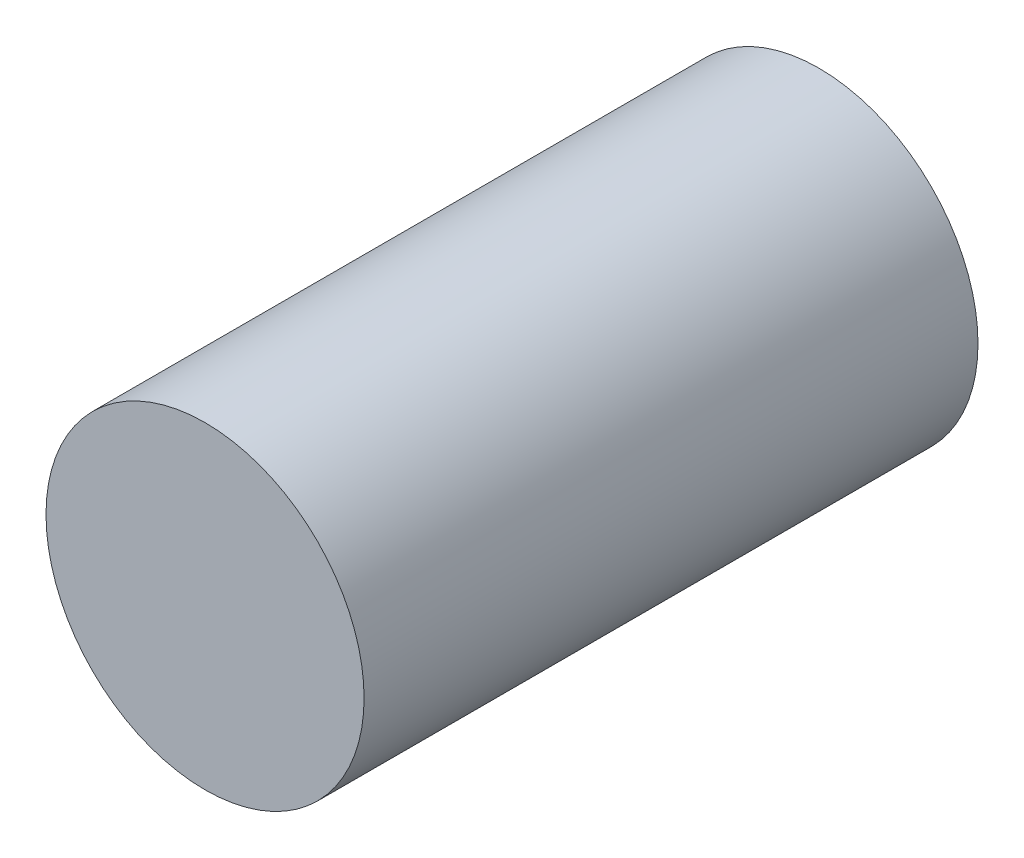
SolidWorks part; units mm, degrees
ref_plane "Płaszczyzna przednia" through (0, 0, 0) normal (0, 0, 1) x (1, 0, 0)
ref_plane "Płaszczyzna górna" through (0, 0, 0) normal (0, 1, 0) x (1, 0, 0)
ref_plane "Płaszczyzna prawa" through (0, 0, 0) normal (1, 0, 0) x (0, 0, -1)
sketch "Sketch1" plane through (0, 0, 0) normal (0, 0, 1) x (1, 0, 0)
  circle A0 centre (0, 0) radius 1
  dimension "D1" = 2
extrude "Boss-Extrude1" add sketch "Sketch1" along normal mid plane 3.86
